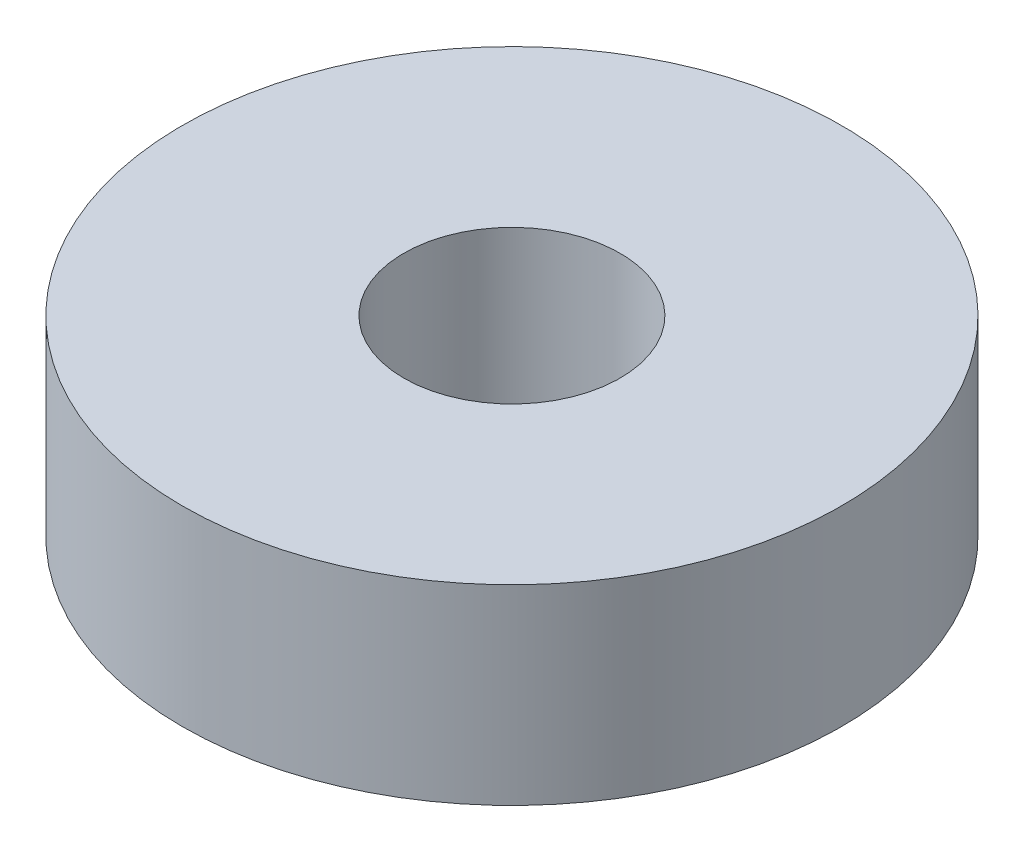
SolidWorks part; units mm, degrees
ref_plane "Front Plane" through (0, 0, 0) normal (0, 0, 1) x (1, 0, 0)
ref_plane "Top Plane" through (0, 0, 0) normal (0, 1, 0) x (1, 0, 0)
ref_plane "Right Plane" through (0, 0, 0) normal (1, 0, 0) x (0, 0, -1)
sketch "Sketch1" plane through (0, 0, 0) normal (0, 1, 0) x (1, 0, 0)
  circle A0 centre (0, 0) radius 15
  circle A1 centre (0, 0) radius 4.925
  dimension "D1" = 30
  dimension "D2" = 9.85
extrude "Boss-Extrude1" add sketch "Sketch1" along normal blind 8.7
